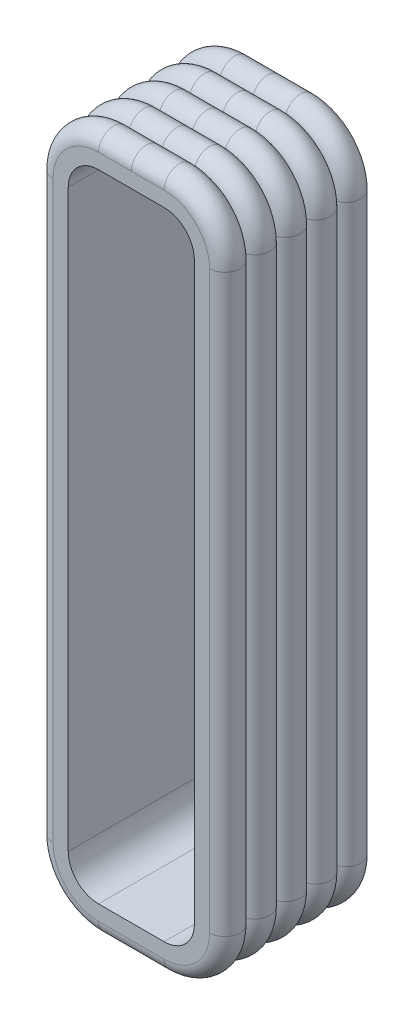
SolidWorks part; units mm, degrees
material "Copper-Cobalt-Beryllium alloy, UNS C17500"
ref_plane "Front Plane" through (0, 0, 0) normal (0, 0, 1) x (1, 0, 0)
ref_plane "Top Plane" through (0, 0, 0) normal (0, 1, 0) x (1, 0, 0)
ref_plane "Right Plane" through (0, 0, 0) normal (1, 0, 0) x (0, 0, -1)
sketch "Sketch1" plane through (0, 0, 0) normal (0, 0, 1) x (1, 0, 0)
  line L0 (-0.925, 2.85) -> (-0.925, -2.85)
  line L1 (-0.325, 3.15) -> (0.325, 3.15)
  line L2 (-0.625, 2.85) -> (-0.625, -2.85)
  line L3 (-0.325, -3.15) -> (0.325, -3.15)
  line L4 (0.625, 2.85) -> (0.625, -2.85)
  line L5 (-0.625, 3.15) -> (0.625, -3.15) construction
  line L6 (-0.625, -3.15) -> (0.625, 3.15) construction
  line L7 (-0.325, -3.45) -> (0.325, -3.45)
  line L8 (0.925, 2.85) -> (0.925, -2.85)
  line L9 (-0.325, 3.45) -> (0.325, 3.45)
  arc A2 (0.325, -3.15) -> (0.625, -2.85) centre (0.325, -2.85) ccw
  arc A3 (-0.625, -2.85) -> (-0.325, -3.15) centre (-0.325, -2.85) ccw
  arc A4 (0.325, 3.15) -> (0.625, 2.85) centre (0.325, 2.85) cw
  arc A5 (-0.325, 3.15) -> (-0.625, 2.85) centre (-0.325, 2.85) ccw
  arc A6 (-0.925, -2.85) -> (-0.325, -3.45) centre (-0.325, -2.85) ccw
  arc A7 (0.325, -3.45) -> (0.925, -2.85) centre (0.325, -2.85) ccw
  arc A8 (0.325, 3.45) -> (0.925, 2.85) centre (0.325, 2.85) cw
  arc A9 (-0.325, 3.45) -> (-0.925, 2.85) centre (-0.325, 2.85) ccw
  point P0 (0, 0)
  dimension "D2" = 0.3
  dimension "D1" = 1.25
  dimension "D3" = 5.7
  dimension "D4" = 0.3
extrude "Boss-Extrude1" add sketch "Sketch1" against normal blind 1.5
sketch "Sketch2" plane through (0, 0, 0) normal (1, 0, 0) x (0, 0, -1)
  line L0 (1.5, 3.45) -> (0, 3.45) construction
  line L1 (0, 3.45) -> (0.3, 3.45) construction
  line L3 (0.3, 3.45) -> (0.3, 3.3)
  line L4 (0, 3.45) -> (0, 3.3)
  line L6 (0, 3.45) -> (0, 3.95)
  line L7 (0, 3.95) -> (0.3, 3.95)
  line L8 (0.3, 3.95) -> (0.3, 3.45)
  arc A0 (0.3, 3.3) -> (0, 3.3) centre (0.15, 3.3) ccw
  dimension "D1" = 0.3
  dimension "D2" = 0.5
sketch "Sketch3" plane through (0, 0, 0) normal (0, 0, 1) x (1, 0, 0)
  line L4 (0.325, 3.45) -> (-0.325, 3.45) construction
  line L5 (-0.925, 2.85) -> (-0.925, -2.85) construction
  line L6 (-0.325, -3.45) -> (0.325, -3.45) construction
  line L7 (0.925, -2.85) -> (0.925, 2.85) construction
  line L8 (0.325, 3.45) -> (-0.325, 3.45)
  line L9 (-0.925, 2.85) -> (-0.925, -2.85)
  line L10 (-0.325, -3.45) -> (0.325, -3.45)
  line L11 (0.925, -2.85) -> (0.925, 2.85)
  arc A4 (-0.325, 3.45) -> (-0.925, 2.85) centre (-0.325, 2.85) ccw construction
  arc A5 (-0.925, -2.85) -> (-0.325, -3.45) centre (-0.325, -2.85) ccw construction
  arc A6 (0.325, -3.45) -> (0.925, -2.85) centre (0.325, -2.85) ccw construction
  arc A7 (0.925, 2.85) -> (0.325, 3.45) centre (0.325, 2.85) ccw construction
  arc A8 (-0.325, 3.45) -> (-0.925, 2.85) centre (-0.325, 2.85) ccw
  arc A9 (-0.925, -2.85) -> (-0.325, -3.45) centre (-0.325, -2.85) ccw
  arc A10 (0.325, -3.45) -> (0.925, -2.85) centre (0.325, -2.85) ccw
  arc A11 (0.925, 2.85) -> (0.325, 3.45) centre (0.325, 2.85) ccw
sweep "Cut-Sweep3" cut profiles "Sketch2" path "Sketch3"
pattern_linear "LPattern1" count 5 spacing 0.3 along (0, 0, -1) of "Cut-Sweep3"
